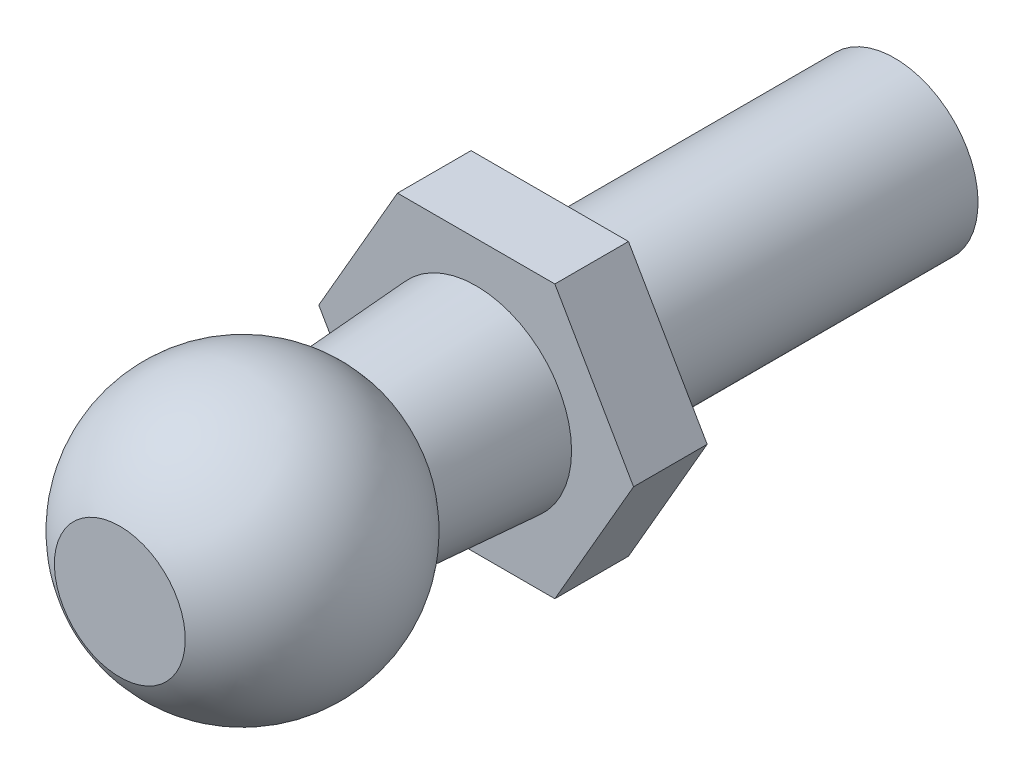
SolidWorks part; units mm, degrees
material "1060 Alloy"
ref_plane "Front Plane" through (0, 0, 0) normal (0, 0, 1) x (1, 0, 0)
ref_plane "Top Plane" through (0, 0, 0) normal (0, 1, 0) x (1, 0, 0)
ref_plane "Right Plane" through (0, 0, 0) normal (1, 0, 0) x (0, 0, -1)
sketch "Sketch1" plane through (0, 0, 0) normal (1, 0, 0) x (0, 0, -1)
  line L0 (0, 0) -> (36.0949, 0)
  line L1 (0, 0) -> (0, 3.048)
  line L2 (10.7584, 4.064) -> (16.6004, 4.445)
  line L3 (16.6004, 4.445) -> (16.6004, 10.16)
  line L4 (16.6004, 10.16) -> (20.0294, 10.16)
  line L5 (20.0294, 10.16) -> (20.0294, 3.8862)
  line L6 (20.0294, 3.8862) -> (36.0949, 3.8862)
  line L7 (36.0949, 3.8862) -> (36.0949, 0)
  arc A0 (10.7584, 4.064) -> (0, 3.048) centre (5.715, 0) ccw
  dimension "D2" = 6.477
  dimension "D1" = 4.064
  dimension "D3" = 5.842
  dimension "D4" = 4.445
  dimension "D5" = 10.16
  dimension "D6" = 3.429
  dimension "D7" = 3.8862
  dimension "D8" = 3.048
  dimension "D9" = 16.0655
revolve "Revolve1" add sketch "Sketch1" angle 360 about L0
sketch "Sketch2" plane through (0, 0, -16.6004) normal (0, 0, 1) x (1, 0, 0)
  line L0 (-3.6662, 6.35) -> (3.6662, 6.35)
  line L1 (3.6662, 6.35) -> (7.3323, 0)
  line L2 (7.3323, 0) -> (3.6662, -6.35)
  line L3 (3.6662, -6.35) -> (-3.6662, -6.35)
  line L4 (-3.6662, -6.35) -> (-7.3323, 0)
  line L5 (-7.3323, 0) -> (-3.6662, 6.35)
  line L6 (-3.6662, 6.35) -> (3.6662, -6.35) construction
  line L7 (-7.3323, 0) -> (7.3323, 0) construction
  line L8 (3.6662, 6.35) -> (-3.6662, -6.35) construction
  circle A0 centre (0, 0) radius 13.9259
  dimension "D1" = 12.7
extrude "Cut-Extrude1" cut sketch "Sketch2" against normal through all
equation "\"D1@Sketch1\"=.32/2"
equation "\"D4@Sketch1\"=.35/2"
equation "\"D2@Sketch1\"=.510/2"
equation "\"D7@Sketch1\"=.306/2"
